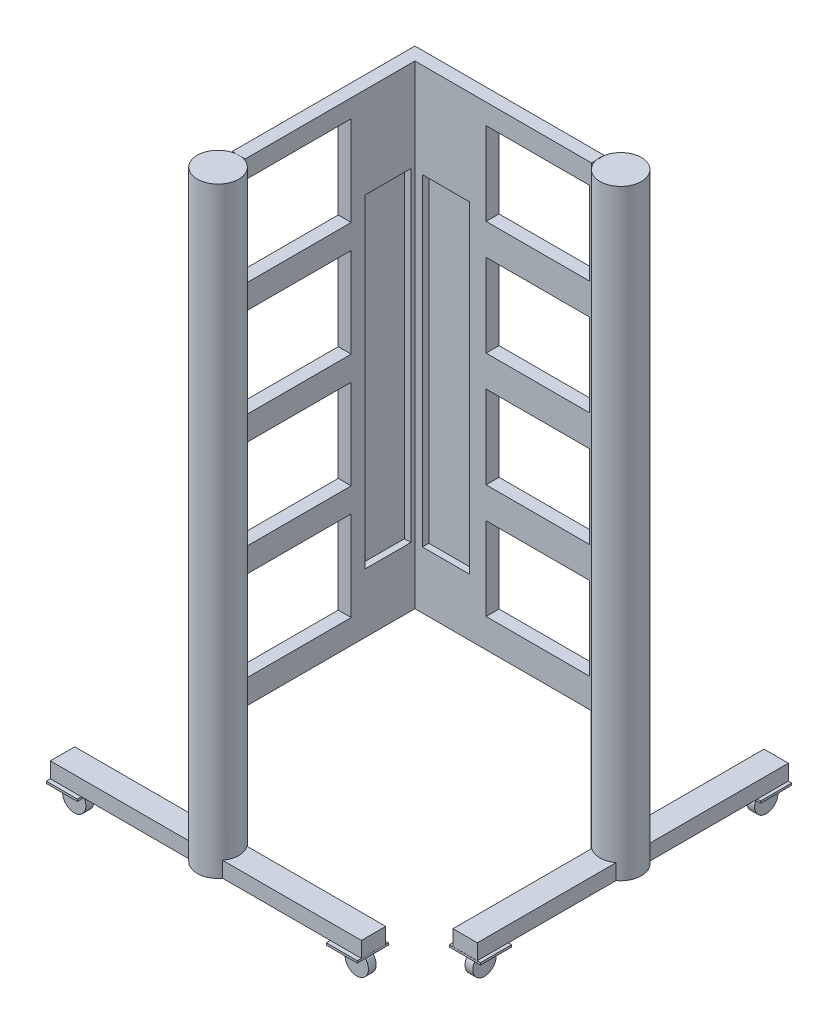
SolidWorks part; units mm, degrees
ref_plane "Alzado" through (0, 0, 0) normal (0, 0, 1) x (1, 0, 0)
ref_plane "Planta" through (0, 0, 0) normal (0, 1, 0) x (1, 0, 0)
ref_plane "Vista lateral" through (0, 0, 0) normal (1, 0, 0) x (0, 0, -1)
sketch "Croquis1" plane through (0, 0, 0) normal (0, 1, 0) x (1, 0, 0)
  line L0 (0, 0) -> (340, 0)
  line L1 (0, -12.5) -> (340.5069, -12.5)
  line L2 (-25, 0) -> (-25, 12.5)
  line L5 (-0.5069, 12.5) -> (340.5069, 12.5)
  line L6 (340.5069, -12.5) -> (340.5069, 12.5)
  line L8 (170, 0) -> (340.5069, -12.5) construction
  line L9 (-0.5069, 0) -> (0, 0)
  line L10 (-25, 0) -> (-25, -340)
  line L11 (-25, -340) -> (0, -340)
  line L12 (0, -12.5) -> (0, -340)
  line L13 (-25, 0) -> (0, -340) construction
  line L14 (-25, -340) -> (-12.5, -170) construction
  line L15 (-25, 12.5) -> (-0.5069, 12.5)
  line L19 (170, 0) -> (340.5069, 12.5) construction
  circle A0 centre (379.7289, 4.6491) radius 40
  circle A1 centre (-12.5, -379.7701) radius 40
  point P4 (0, 0)
  point P8 (-12.5, -170)
  point P10 (170, 0)
  dimension "D3" = 80
  dimension "D4" = 80
  dimension "D1" = 340
  dimension "D5" = 25
extrude "Saliente-Extruir1" add sketch "Croquis1" along normal blind 1160
sketch "Croquis2" plane through (-25, 0, 0) normal (-1, 0, 0) x (0, 0, 1)
  line L0 (340, 1160) -> (340, 0) construction
  line L1 (135.3987, 1124.9201) -> (340, 1124.9201)
  line L2 (135.3987, 1124.9201) -> (135.3987, 951.6666)
  line L3 (135.3987, 951.6666) -> (340, 951.6666)
  line L4 (340, 1124.9201) -> (340, 951.6666)
  line L5 (135.3987, 1124.9201) -> (340, 951.6666) construction
  line L6 (135.3987, 951.6666) -> (340, 1124.9201) construction
  point P0 (237.6994, 1038.2934)
  point P5 (164.5227, 1027.3504)
  point P6 (340, 921.3365)
  point P9 (0, 0)
  point P10 (135.3987, 951.6666)
extrude "Cortar-Extruir1" cut sketch "Croquis2" against normal blind 150
pattern_linear "MatrizL1" count 5 spacing 220 along (0, -1, 0) of "Cortar-Extruir1"
sketch "Croquis3" plane through (-25, 0, 0) normal (-1, 0, 0) x (0, 0, 1)
  line L1 (20.2712, 984.2019) -> (108.7651, 984.2019)
  line L2 (20.2712, 984.2019) -> (20.2712, 359.5234)
  line L3 (20.2712, 359.5234) -> (108.7651, 359.5234)
  line L4 (108.7651, 984.2019) -> (108.7651, 359.5234)
  line L5 (20.2712, 984.2019) -> (108.7651, 359.5234) construction
  line L6 (20.2712, 359.5234) -> (108.7651, 984.2019) construction
  point P0 (64.5182, 671.8627)
  point P5 (55.6585, 637.258)
  point P6 (20.2712, 344.8642)
  point P7 (0, 0)
  point P8 (108.7651, 359.5234)
extrude "Cortar-Extruir3" cut sketch "Croquis3" against normal blind 150
sketch "Croquis4" plane through (0, 0, -12.5) normal (0, 0, -1) x (-1, 0, 0)
  line L1 (-105.5427, 977.4009) -> (-14.3643, 977.4009)
  line L2 (-105.5427, 977.4009) -> (-105.5427, 355.3053)
  line L3 (-105.5427, 355.3053) -> (-14.3643, 355.3053)
  line L4 (-14.3643, 977.4009) -> (-14.3643, 355.3053)
  line L5 (-105.5427, 977.4009) -> (-14.3643, 355.3053) construction
  line L6 (-105.5427, 355.3053) -> (-14.3643, 977.4009) construction
  point P0 (-59.9535, 666.3531)
  point P5 (-14.3643, 977.4009)
  point P6 (-105.5427, 355.3053)
extrude "Cortar-Extruir4" cut sketch "Croquis4" against normal blind 150
sketch "Croquis5" plane through (-25, 0, 0) normal (-1, 0, 0) x (0, 0, 1)
  line L0 (340, 244.9201) -> (-12.5, 244.9201)
  line L1 (-12.5, 1160) -> (-12.5, 0) construction
  line L2 (-12.5, 244.9201) -> (-12.5, 0)
  line L3 (-12.5, 0) -> (340, 0)
  line L4 (340, 0) -> (340, 244.9201)
extrude "Cortar-Extruir5" cut sketch "Croquis5" against normal blind 365
sketch "Croquis6" plane through (0, 0, -12.5) normal (0, 0, -1) x (-1, 0, 0)
  line L1 (-336.3067, 1120.6416) -> (-137.2709, 1120.6416)
  line L2 (-336.3067, 1120.6416) -> (-336.3067, 960.6416)
  line L3 (-336.3067, 960.6416) -> (-137.2709, 960.6416)
  line L4 (-137.2709, 1120.6416) -> (-137.2709, 960.6416)
  line L5 (-336.3067, 1120.6416) -> (-137.2709, 960.6416) construction
  line L6 (-336.3067, 960.6416) -> (-137.2709, 1120.6416) construction
  point P0 (-236.7888, 1040.6416)
  point P5 (-249.0074, 1031.1282)
  point P6 (-129.1694, 960.7762)
  point P7 (-137.2709, 960.6416)
  dimension "D1" = 160
extrude "Cortar-Extruir6" cut sketch "Croquis6" against normal blind 365
pattern_linear "MatrizL2" count 4 spacing 220 along (0, -1, 0) of "Cortar-Extruir6"
ref_plane "Plano1" through (0, 0, 0) normal (0, 0, -1) x (-1, 0, 0)
sketch "Croquis7" plane through (0, 0, 0) normal (0, 0, -1) x (-1, 0, 0)
  line L0 (-105.5427, 977.4009) -> (-105.5427, 355.3053)
  line L1 (-105.5427, 355.3053) -> (-14.3643, 355.3053)
  line L2 (-14.3643, 355.3053) -> (-14.3643, 977.4009)
  line L3 (-14.3643, 977.4009) -> (-105.5427, 977.4009)
extrude "Saliente-Extruir2" add sketch "Croquis7" along normal blind 1
ref_plane "Plano2" through (-12.5, 0, 0) normal (-1, 0, 0) x (0, 0, 1)
sketch "Croquis8" plane through (-12.5, 0, 0) normal (-1, 0, 0) x (0, 0, 1)
  line L0 (20.2712, 984.2019) -> (108.7651, 984.2019)
  line L1 (108.7651, 984.2019) -> (108.7651, 359.5234)
  line L2 (108.7651, 359.5234) -> (20.2712, 359.5234)
  line L3 (20.2712, 359.5234) -> (20.2712, 984.2019)
extrude "Saliente-Extruir3" add sketch "Croquis8" along normal blind 1
sketch "Croquis9" plane through (0, 0, 0) normal (0, -1, 0) x (1, 0, 0)
  line L1 (403.2289, -304.6491) -> (356.2289, -304.6491)
  line L2 (403.2289, -304.6491) -> (403.2289, 295.3509)
  line L3 (403.2289, 295.3509) -> (356.2289, 295.3509)
  line L4 (356.2289, -304.6491) -> (356.2289, 295.3509)
  line L5 (403.2289, -304.6491) -> (356.2289, 295.3509) construction
  line L6 (403.2289, 295.3509) -> (356.2289, -304.6491) construction
  line L7 (287.5, 403.2701) -> (-312.5, 403.2701)
  line L8 (287.5, 403.2701) -> (287.5, 356.2701)
  line L9 (287.5, 356.2701) -> (-312.5, 356.2701)
  line L10 (-312.5, 403.2701) -> (-312.5, 356.2701)
  line L11 (287.5, 403.2701) -> (-312.5, 356.2701) construction
  line L12 (287.5, 356.2701) -> (-312.5, 403.2701) construction
  point P0 (379.7289, -4.6491)
  point P6 (-12.5, 379.7701)
  dimension "D1" = 47
  dimension "D2" = 47
  dimension "D3" = 600
  dimension "D4" = 600
extrude "Saliente-Extruir4" add sketch "Croquis9" against normal blind 30
sketch "Croquis10" plane through (0, 0, 0) normal (0, -1, 0) x (1, 0, 0)
  line L0 (-12.5, 419.7701) -> (-12.5, 379.7701) construction
  line L1 (287.5274, 351.0453) -> (227.5274, 351.0453)
  line L2 (287.5274, 351.0453) -> (287.5274, 411.0453)
  line L3 (287.5274, 411.0453) -> (227.5274, 411.0453)
  line L4 (227.5274, 351.0453) -> (227.5274, 411.0453)
  line L5 (287.5274, 351.0453) -> (227.5274, 411.0453) construction
  line L6 (287.5274, 411.0453) -> (227.5274, 351.0453) construction
  line L7 (-312.5274, 411.0453) -> (-252.5274, 351.0453) construction
  line L8 (-312.5274, 351.0453) -> (-252.5274, 411.0453) construction
  line L9 (-252.5274, 351.0453) -> (-252.5274, 411.0453)
  line L10 (-312.5274, 411.0453) -> (-252.5274, 411.0453)
  line L11 (-312.5274, 351.0453) -> (-312.5274, 411.0453)
  line L12 (-312.5274, 351.0453) -> (-252.5274, 351.0453)
  line L13 (419.7289, -4.6491) -> (379.7289, -4.6491) construction
  line L14 (409.4857, 235.5459) -> (349.4857, 235.5459)
  line L15 (409.4857, 235.5459) -> (409.4857, 295.5459)
  line L16 (409.4857, 295.5459) -> (349.4857, 295.5459)
  line L17 (349.4857, 235.5459) -> (349.4857, 295.5459)
  line L18 (409.4857, 235.5459) -> (349.4857, 295.5459) construction
  line L19 (409.4857, 295.5459) -> (349.4857, 235.5459) construction
  line L20 (409.4857, -304.8441) -> (349.4857, -244.8441) construction
  line L21 (409.4857, -244.8441) -> (349.4857, -304.8441) construction
  line L22 (349.4857, -244.8441) -> (349.4857, -304.8441)
  line L23 (409.4857, -304.8441) -> (349.4857, -304.8441)
  line L24 (409.4857, -244.8441) -> (409.4857, -304.8441)
  line L25 (409.4857, -244.8441) -> (349.4857, -244.8441)
  arc A0 (19.869, 403.2701) -> (-44.869, 403.2701) centre (-12.5, 379.7701) ccw construction
  arc A1 (403.2289, -37.0181) -> (403.2289, 27.7199) centre (379.7289, -4.6491) ccw construction
  point P0 (257.5274, 381.0453)
  point P15 (-282.5274, 381.0453)
  point P16 (379.4857, 265.5459)
  point P31 (379.4857, -274.8441)
  dimension "D1" = 60
  dimension "D2" = 60
  dimension "D3" = 60
  dimension "D4" = 60
extrude "Saliente-Extruir5" add sketch "Croquis10" along normal blind 4
ref_plane "Plano3" through (0, 0, 379.7701) normal (0, 0, -1) x (-1, 0, 0)
sketch "Croquis11" plane through (0, 0, 379.7701) normal (0, 0, -1) x (-1, 0, 0)
  line L0 (0, 0) -> (0, -22.5097) construction
  circle A0 centre (282.3647, -27.3842) radius 22.5
  circle A1 centre (-262.5764, -27.3842) radius 22.5
  dimension "D1" = 45
  dimension "D2" = 45
extrude "Saliente-Extruir6" add sketch "Croquis11" along normal blind 7.5 and the other way blind 7.5 separate body
ref_plane "Plano4" through (379.7289, 0, 0) normal (1, 0, 0) x (0, 0, -1)
sketch "Croquis12" plane through (379.7289, 0, 0) normal (1, 0, 0) x (0, 0, -1)
  circle A0 centre (-265.5459, -26.6593) radius 22.5
  circle A1 centre (278.013, -26.6593) radius 22.5
  dimension "D1" = 45
  dimension "D2" = 45
extrude "Saliente-Extruir7" add sketch "Croquis12" along normal blind 7.5 and the other way blind 7.5 separate body
